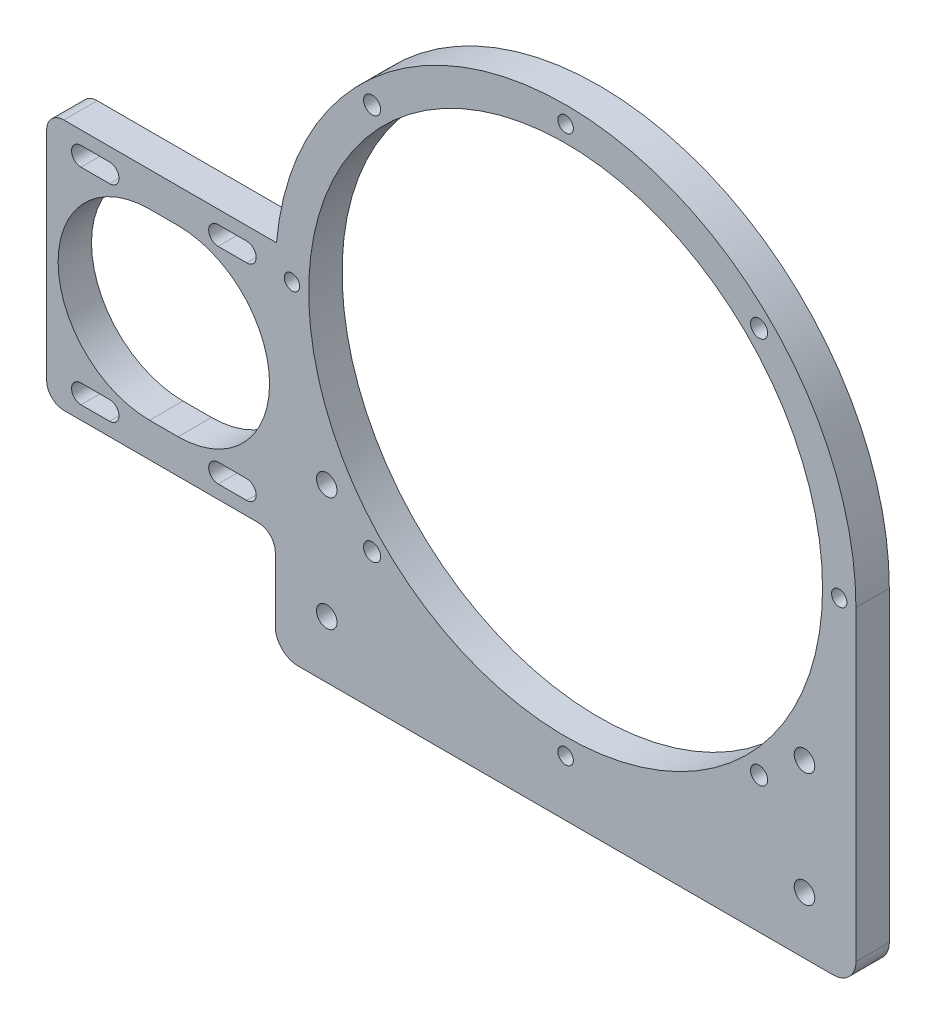
SolidWorks part; units mm, degrees
material "Balsa"
ref_plane "Front Plane" through (0, 0, 0) normal (0, 0, 1) x (1, 0, 0)
ref_plane "Top Plane" through (0, 0, 0) normal (0, 1, 0) x (1, 0, 0)
ref_plane "Right Plane" through (0, 0, 0) normal (1, 0, 0) x (0, 0, -1)
sketch "Sketch1" plane through (0, 0, 0) normal (0, 0, 1) x (1, 0, 0)
  line L0 (-50.8, 0) -> (-50.8, -57.658)
  line L1 (-50.8, 0) -> (-44.958, 0) construction
  line L2 (0, 0) -> (0, -57.658) construction
  line L3 (0, 0) -> (0, -62.9374) construction
  line L4 (50.8, 0) -> (50.8, -57.658)
  line L5 (-33.8556, 33.8556) -> (0, 0) construction
  line L8 (0, 0) -> (0, 47.879) construction
  line L12 (-50.8, -57.658) -> (0, -57.658)
  line L13 (-41.8, -57.658) -> (-41.8, -47.658) construction
  line L14 (-41.8, -47.658) -> (-41.8, -27.658) construction
  line L19 (0, -57.658) -> (50.8, -57.658)
  circle A1 centre (0, 0) radius 44.958
  arc A2 (-50.8, 0) -> (50.8, 0) centre (0, 0) cw
  circle A3 centre (-47.879, 0) radius 1.35
  circle A4 centre (0, 47.879) radius 1.35
  circle A6 centre (47.879, 0) radius 1.35
  circle A7 centre (0, -47.879) radius 1.35
  circle A10 centre (-41.8, -27.658) radius 1.8
  circle A11 centre (-33.8556, 33.8556) radius 1.5
  circle A12 centre (33.8556, 33.8556) radius 1.5
  circle A13 centre (33.8556, -33.8556) radius 1.5
  circle A14 centre (-33.8556, -33.8556) radius 1.5
  circle A15 centre (-41.8, -47.658) radius 1.8
  circle A16 centre (41.8, -47.658) radius 1.8
  circle A17 centre (41.8, -27.658) radius 1.8
  point P29 (0, 0)
  point P46 (0, 0)
  dimension "D2" = 89.916
  dimension "D5" = 2.7
  dimension "D6" = 4
  dimension "D7" = 45
  dimension "D10" = 62.9374
  dimension "D14" = 3
  dimension "D17" = 3.6
  dimension "D3" = 57.658
  dimension "D4" = 101.6
  dimension "D18" = 20
  dimension "D19" = 10
  dimension "D20" = 9
  dimension "D15" = 4
extrude "Boss-Extrude1" add sketch "Sketch1" along normal blind 5.842
fillet "Fillet1" radius 4 2 edges at (50.8, -57.658, 2.921) (-50.8, -57.658, 2.921)
sketch "Sketch2" plane through (0, 0, 5.842) normal (0, 0, 1) x (1, 0, 0)
  line L0 (-50.5923, 4.5885) -> (-90.8, 4.5885)
  line L1 (-79.8, 0.5885) -> (-67.8, -17.4115) construction
  line L2 (-90.8, 4.5885) -> (-90.8, -39.4115)
  line L3 (-90.8, -39.4115) -> (-50.8, -39.4115)
  line L5 (-50.5923, 4.5885) -> (-50.8, -39.4115)
  line L6 (-67.8, -17.4115) -> (-72.8, -17.4115) construction
  line L7 (-67.8, -33.4115) -> (-72.8, -33.4115)
  line L8 (-79.8, 0.5885) -> (-79.8, -35.4115) construction
  line L9 (-79.8, -35.4115) -> (-55.8, -35.4115) construction
  line L10 (-55.8, -35.4115) -> (-55.8, 0.5885) construction
  line L11 (-55.8, 0.5885) -> (-79.8, 0.5885) construction
  line L12 (-67.8, -17.4115) -> (-79.8, -35.4115) construction
  line L13 (-55.8, 0.5885) -> (-67.8, -17.4115) construction
  line L14 (-67.8, -17.4115) -> (-55.8, -35.4115) construction
  line L16 (-67.8, -17.4115) -> (0, 0) construction
  line L17 (-79.8, 0.5885) -> (-84.8, 0.5885) construction
  line L18 (-67.8, -1.4115) -> (-72.8, -1.4115)
  line L19 (-79.8, -1.0615) -> (-84.8, -1.0615)
  line L20 (-79.8, 2.2385) -> (-84.8, 2.2385)
  line L21 (-55.8, 0.5885) -> (-60.8, 0.5885) construction
  line L22 (-55.8, -1.0615) -> (-60.8, -1.0615)
  line L23 (-55.8, 2.2385) -> (-60.8, 2.2385)
  line L24 (-50.8, 0) -> (-50.8, -53.658) construction
  line L25 (-79.8, -35.4115) -> (-84.8, -35.4115) construction
  line L26 (-79.8, -37.0615) -> (-84.8, -37.0615)
  line L27 (-79.8, -33.7615) -> (-84.8, -33.7615)
  line L28 (-55.8, -35.4115) -> (-60.8, -35.4115) construction
  line L29 (-55.8, -37.0615) -> (-60.8, -37.0615)
  line L30 (-55.8, -33.7615) -> (-60.8, -33.7615)
  arc A0 (-67.8, -33.4115) -> (-67.8, -1.4115) centre (-67.8, -17.4115) ccw
  arc A1 (-79.8, -1.0615) -> (-79.8, 2.2385) centre (-79.8, 0.5885) ccw
  arc A2 (-84.8, 2.2385) -> (-84.8, -1.0615) centre (-84.8, 0.5885) ccw
  arc A3 (-55.8, -1.0615) -> (-55.8, 2.2385) centre (-55.8, 0.5885) ccw
  arc A4 (-60.8, 2.2385) -> (-60.8, -1.0615) centre (-60.8, 0.5885) ccw
  arc A5 (-72.8, -1.4115) -> (-72.8, -33.4115) centre (-72.8, -17.4115) ccw
  arc A6 (50.8, 0) -> (-50.8, 0) centre (0, 0) ccw construction
  circle A7 centre (-67.8, -17.4115) radius 16 construction
  arc A8 (-79.8, -37.0615) -> (-79.8, -33.7615) centre (-79.8, -35.4115) ccw
  arc A9 (-84.8, -33.7615) -> (-84.8, -37.0615) centre (-84.8, -35.4115) ccw
  arc A10 (-55.8, -37.0615) -> (-55.8, -33.7615) centre (-55.8, -35.4115) ccw
  arc A11 (-60.8, -33.7615) -> (-60.8, -37.0615) centre (-60.8, -35.4115) ccw
  point P1 (-70.3, -17.4115)
  point P6 (-82.3, 0.5885)
  point P25 (-82.3, -35.4115)
  point P27 (-58.3, 0.5885)
  point P44 (-58.3, -35.4115)
  dimension "D2" = 1.65
  dimension "D9" = 32
  dimension "D6" = 16
  dimension "D3" = 70
  dimension "D4" = 4
  dimension "D5" = 24
  dimension "D7" = 4
  dimension "D8" = 17
  dimension "D10" = 6
  dimension "D12" = 5
  dimension "D13" = 5
  dimension "D14" = 36
extrude "Boss-Extrude2" add sketch "Sketch2" against normal through all
fillet "Fillet2" radius 3 3 edges at (-50.8, -39.4115, 2.921) (-90.8, -39.4115, 2.921) (-90.8, 4.5885, 2.921)
